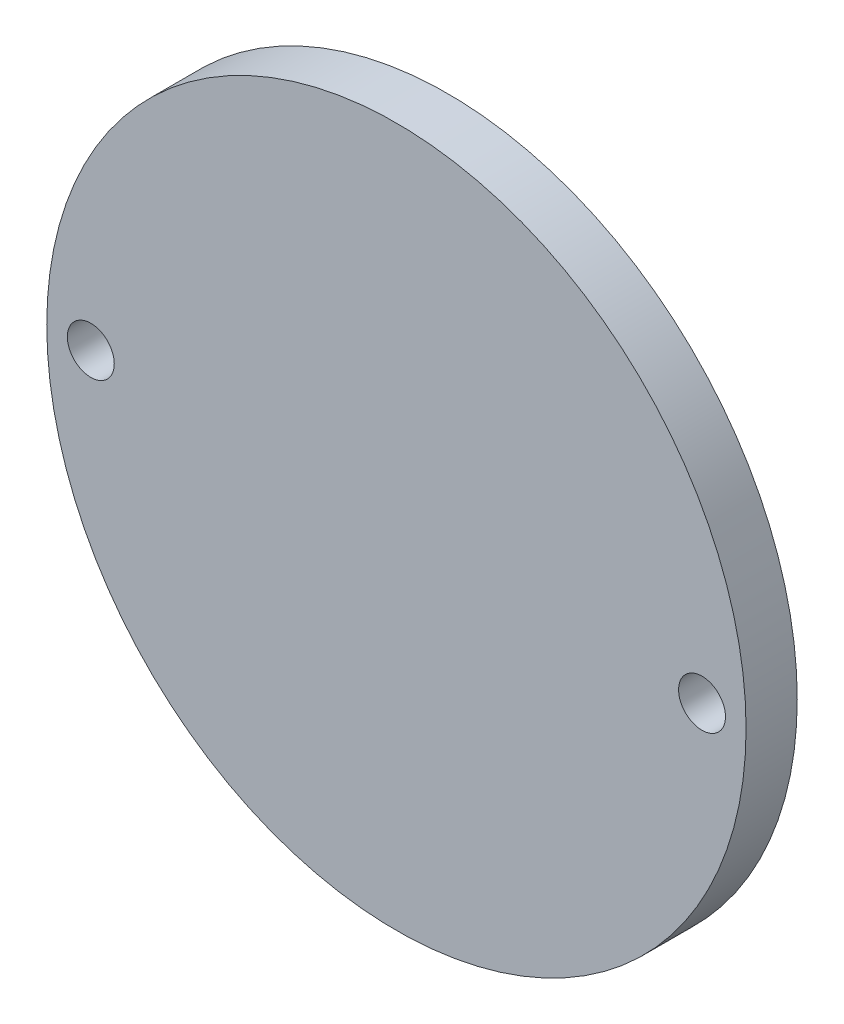
SolidWorks part; units mm, degrees
ref_plane "Front Plane" through (0, 0, 0) normal (0, 0, 1) x (1, 0, 0)
ref_plane "Top Plane" through (0, 0, 0) normal (0, 1, 0) x (1, 0, 0)
ref_plane "Right Plane" through (0, 0, 0) normal (1, 0, 0) x (0, 0, -1)
sketch "Sketch1" plane through (0, 0, 0) normal (0, 0, 1) x (1, 0, 0)
  circle A0 centre (0, 0) radius 24.6
  dimension "D1" = 49.2
extrude "Boss-Extrude1" add sketch "Sketch1" along normal blind 3.6
sketch "Sketch2" plane through (0, 0, 3.6) normal (0, 0, 1) x (1, 0, 0)
  line L0 (-21.5, 0) -> (21.5, 0) construction
  circle A0 centre (-21.5, 0) radius 1.65
  circle A1 centre (21.5, 0) radius 1.65
  point P4 (0, 0)
  dimension "D2" = 3.3
  dimension "D1" = 43
extrude "Cut-Extrude1" cut sketch "Sketch2" against normal through all
